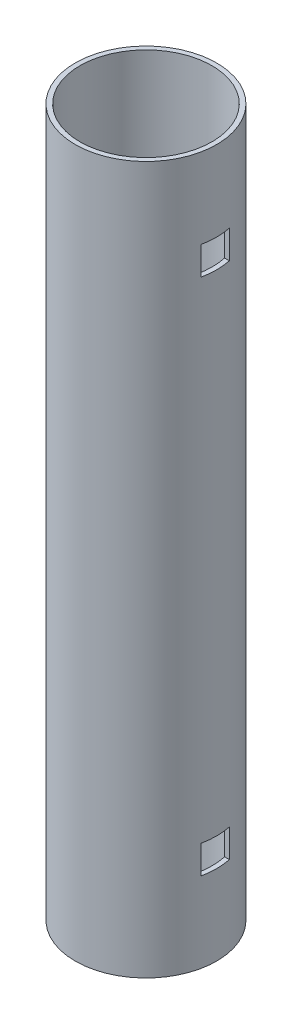
SolidWorks part; units mm, degrees
ref_plane "Front Plane" through (0, 0, 0) normal (0, 0, 1) x (1, 0, 0)
ref_plane "Top Plane" through (0, 0, 0) normal (0, 1, 0) x (1, 0, 0)
ref_plane "Right Plane" through (0, 0, 0) normal (1, 0, 0) x (0, 0, -1)
sketch "Sketch1" plane through (0, 0, 0) normal (0, 1, 0) x (1, 0, 0)
  circle A0 centre (0, 0) radius 14
  circle A1 centre (0, 0) radius 15
  dimension "D1" = 30
  dimension "D2" = 28
extrude "Boss-Extrude1" add sketch "Sketch1" along normal blind 150
sketch "Sketch2" plane through (0, 0, 0) normal (1, 0, 0) x (0, 0, -1)
  line L2 (-3, 133) -> (3, 133)
  line L3 (-3, 133) -> (-3, 127)
  line L4 (-3, 127) -> (3, 127)
  line L5 (3, 133) -> (3, 127)
  line L6 (-3, 23) -> (3, 23)
  line L7 (-3, 23) -> (-3, 17)
  line L8 (-3, 17) -> (3, 17)
  line L9 (3, 23) -> (3, 17)
extrude "Cut-Extrude1" cut sketch "Sketch2" against normal mid plane 30
